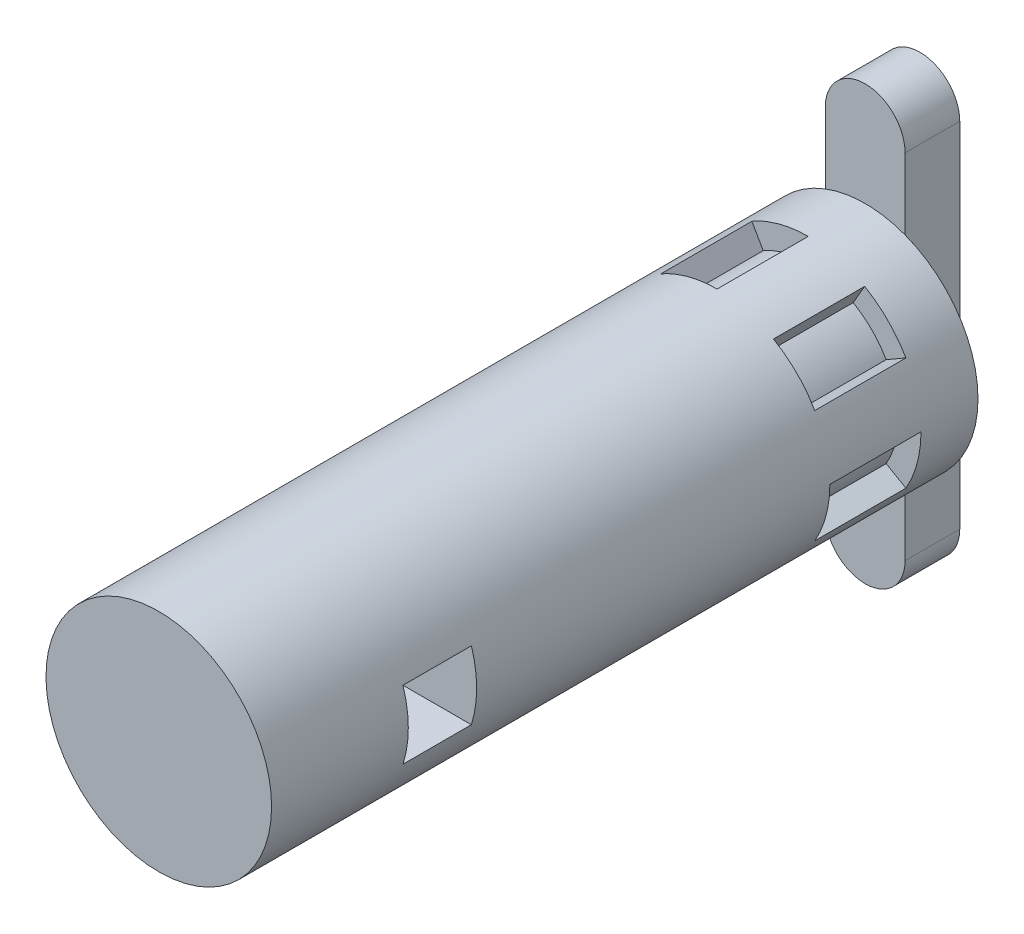
SolidWorks part; units mm, degrees
material "ABS"
ref_plane "前视基准面" through (0, 0, 0) normal (0, 0, 1) x (1, 0, 0)
ref_plane "上视基准面" through (0, 0, 0) normal (0, 1, 0) x (1, 0, 0)
ref_plane "右视基准面" through (0, 0, 0) normal (1, 0, 0) x (0, 0, -1)
sketch "草图1" plane through (0, 0, 0) normal (0, 0, 1) x (1, 0, 0)
  circle A0 centre (0, 0) radius 4.95
  dimension "D1" = 9.9
extrude "凸台-拉伸1" add sketch "草图1" along normal blind 4.5
sketch "草图2" plane through (0, 0, 0) normal (0, 0, -1) x (-1, 0, 0)
  line L0 (0, 4.95) -> (0, 3.95)
  line L1 (1.975, 3.4208) -> (2.475, 4.2868)
  arc A0 (0, 4.95) -> (2.475, 4.2868) centre (0, 0) cw
  circle A1 centre (0, 0) radius 4.95 construction
  arc A2 (0, 3.95) -> (1.975, 3.4208) centre (0, 0) cw
  dimension "D1" = 30
  dimension "D2" = 1
extrude "切除-拉伸1" cut sketch "草图2" against normal blind 2
pattern_circular "阵列(圆周)1" count 6 over 360 about axis through (0, 0, 0) along (0, 0, 1) of "切除-拉伸1"
mirror "镜向1" about plane through (0, 0, 0) normal (0, 0, 1) of "凸台-拉伸1", "切除-拉伸1", "阵列(圆周)1"
sketch "草图3" plane through (0, 0, -4.5) normal (0, 0, -1) x (-1, 0, 0)
  line L0 (0, 7.75) -> (0, -7.75) construction
  line L1 (1.75, 7.75) -> (1.75, -7.75)
  line L2 (-1.75, 7.75) -> (-1.75, -7.75)
  arc A0 (1.75, 7.75) -> (-1.75, 7.75) centre (0, 7.75) ccw
  arc A1 (-1.75, -7.75) -> (1.75, -7.75) centre (0, -7.75) ccw
  point P3 (0, 0)
  point P9 (0, 9.5)
  point P10 (0, -9.5)
  dimension "D1" = 19
  dimension "D2" = 3.5
extrude "凸台-拉伸2" add sketch "草图3" along normal blind 2.4
sketch "草图5" plane through (0, 0, 4.5) normal (0, 0, 1) x (1, 0, 0)
  circle A1 centre (0, 0) radius 4.95
  circle A2 centre (0, 0) radius 4.95
  dimension "D1" = 0
extrude "凸台-拉伸3" add sketch "草图5" along normal blind 22
sketch "草图6" plane through (0, 0, 0) normal (1, 0, 0) x (0, 0, -1)
  line L0 (-26.5, 4.95) -> (-26.5, -4.95) construction
  line L1 (-20.5, -1.5) -> (-17.5, -1.5)
  line L2 (-20.5, -1.5) -> (-20.5, 1.5)
  line L3 (-20.5, 1.5) -> (-17.5, 1.5)
  line L4 (-17.5, -1.5) -> (-17.5, 1.5)
  line L5 (-20.5, -1.5) -> (-17.5, 1.5) construction
  line L6 (-20.5, 1.5) -> (-17.5, -1.5) construction
  point P0 (-19, 0)
  dimension "D1" = 7.5
  dimension "D2" = 3
  dimension "D3" = 3
extrude "切除-拉伸2" cut sketch "草图6" against normal through all both and the other way through all
